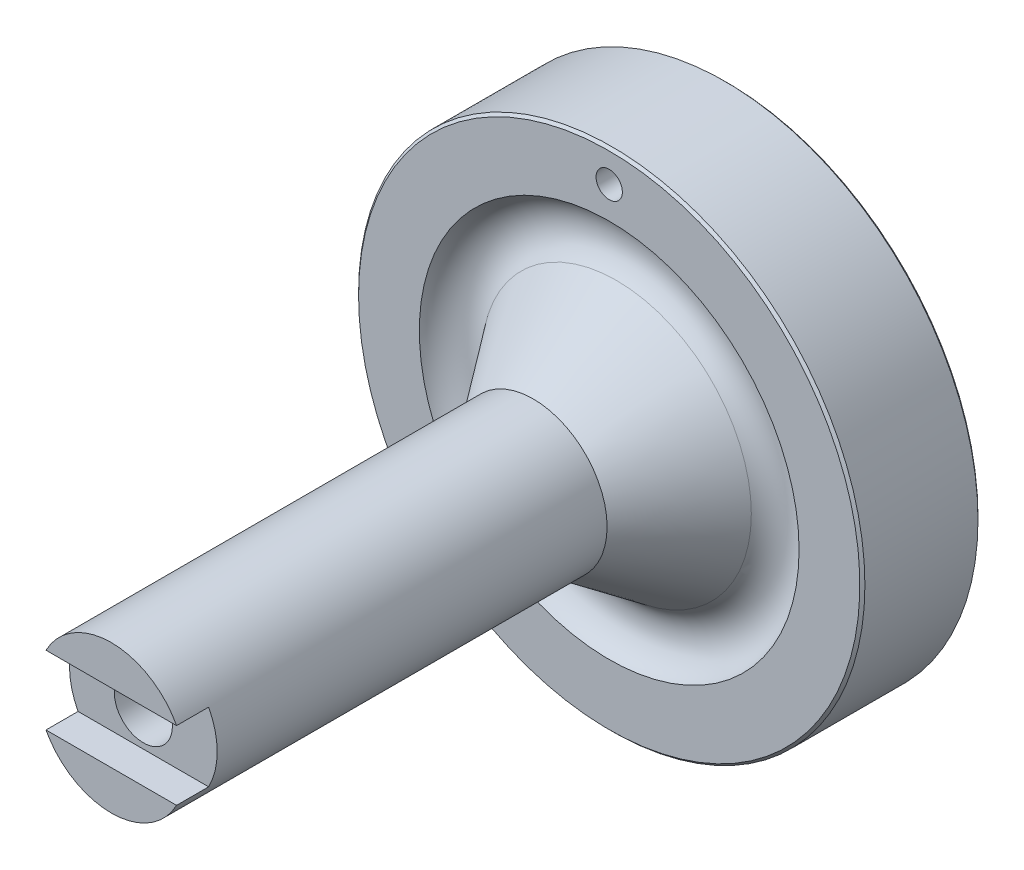
SolidWorks part; units mm, degrees
material "Malleable Cast Iron"
ref_plane "Front Plane" through (0, 0, 0) normal (0, 0, 1) x (1, 0, 0)
ref_plane "Top Plane" through (0, 0, 0) normal (0, 1, 0) x (1, 0, 0)
ref_plane "Right Plane" through (0, 0, 0) normal (1, 0, 0) x (0, 0, -1)
sketch "Sketch1" plane through (0, 0, 0) normal (1, 0, 0) x (0, 0, -1)
  line L0 (0, 0) -> (178.9077, 0) construction
  line L1 (0, 8.7376) -> (0, 22.225)
  line L2 (0, 22.225) -> (127, 22.225)
  line L3 (127, 22.225) -> (152.057, 40.5809)
  line L4 (149.86, 57.15) -> (149.86, 76.2)
  line L5 (149.86, 76.2) -> (185.42, 76.2)
  line L6 (185.42, 76.2) -> (185.42, 57.15)
  line L7 (185.42, 57.15) -> (165.9838, 42.9117)
  line L8 (177.4952, 15.875) -> (177.4952, 8.7376)
  line L9 (177.4952, 8.7376) -> (0, 8.7376)
  line L10 (0, 22.225) -> (0, 0) construction
  line L11 (164.8775, 28.4927) -> (177.4952, 15.875)
  arc A0 (152.057, 40.5809) -> (149.86, 57.15) centre (146.4281, 48.2648) ccw
  arc A2 (165.9838, 42.9117) -> (164.8775, 28.4927) centre (171.6127, 35.2279) ccw
  dimension "D1" = 152.4
  dimension "D11" = 9.525
  dimension "D13" = 45
  dimension "D14" = 9.525
  dimension "D2" = 44.45
  dimension "D3" = 31.75
  dimension "D4" = 17.4752
  dimension "D5" = 22.86
  dimension "D6" = 35.56
  dimension "D7" = 19.05
  dimension "D8" = 19.05
  dimension "D9" = 127
  dimension "D10" = 6.35
  dimension "D12" = 7.9248
revolve "Revolve1" add sketch "Sketch1" angle 360 about L0
chamfer "Chamfer1" distance 0.762 angle 45 2 edges at (76.2, 0, -185.42) (76.2, 0, -149.86)
sketch "Sketch2" plane through (0, 0, 0) normal (1, 0, 0) x (0, 0, -1)
  line L0 (54.7462, 0) -> (-54.7462, 0) construction
  line L1 (9.652, -10.3886) -> (0, -10.3886)
  line L2 (9.652, -10.3886) -> (9.652, 10.3886)
  line L3 (9.652, 10.3886) -> (0, 10.3886)
  line L4 (0, -10.3886) -> (0, 10.3886)
  line L5 (9.652, -10.3886) -> (0, 10.3886) construction
  line L6 (9.652, 10.3886) -> (0, -10.3886) construction
  line L7 (0, 54.9142) -> (0, -54.9142) construction
  point P0 (4.826, 0)
  dimension "D1" = 9.652
  dimension "D2" = 20.7772
extrude "Cut-Extrude1" cut sketch "Sketch2" against normal through all both and the other way through all
sketch "Sketch3" plane through (0, 0, -185.42) normal (0, 0, -1) x (-1, 0, 0)
  line L0 (0, 76.2) -> (0, 57.15) construction
  circle A0 centre (0, 66.675) radius 3.9624
  circle A1 centre (0, 0) radius 76.2 construction
  circle A2 centre (0, 0) radius 57.15 construction
  dimension "D1" = 7.9248
extrude "Cut-Extrude2" cut sketch "Sketch3" against normal through all
